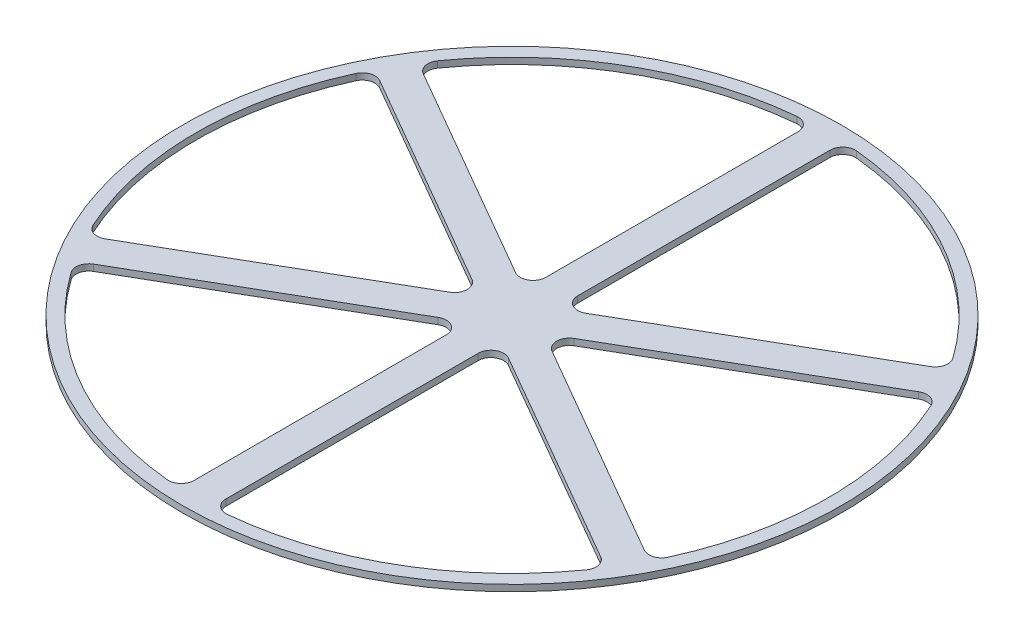
SolidWorks part; units mm, degrees
ref_plane "Front Plane" through (0, 0, 0) normal (0, 0, 1) x (1, 0, 0)
ref_plane "Top Plane" through (0, 0, 0) normal (0, 1, 0) x (1, 0, 0)
ref_plane "Right Plane" through (0, 0, 0) normal (1, 0, 0) x (0, 0, -1)
sketch "Sketch2" plane through (0, 0, 0) normal (0, 1, 0) x (1, 0, 0)
  line L0 (110.1965, 70.9543) -> (6.35, 10.9985)
  line L2 (-6.35, 130.9101) -> (-6.35, 10.9985)
  line L4 (6.35, 130.9101) -> (6.35, 10.9985)
  line L5 (116.5465, 59.9558) -> (12.7, 0)
  line L6 (116.5465, -59.9558) -> (12.7, 0)
  line L7 (110.1965, -70.9543) -> (6.35, -10.9985)
  line L8 (6.35, -130.9101) -> (6.35, -10.9985)
  line L9 (-6.35, -130.9101) -> (-6.35, -10.9985)
  line L10 (-110.1965, -70.9543) -> (-6.35, -10.9985)
  line L11 (-116.5465, -59.9558) -> (-12.7, 0)
  line L12 (-116.5465, 59.9558) -> (-12.7, 0)
  line L13 (-110.1965, 70.9543) -> (-6.35, 10.9985)
  arc A1 (6.35, 130.9101) -> (-6.35, 130.9101) centre (0, 0) ccw
  arc A4 (116.5465, 59.9558) -> (110.1965, 70.9543) centre (0, 0) ccw
  arc A6 (110.1965, -70.9543) -> (116.5465, -59.9558) centre (0, 0) ccw
  arc A8 (-6.35, -130.9101) -> (6.35, -130.9101) centre (0, 0) ccw
  arc A10 (-116.5465, -59.9558) -> (-110.1965, -70.9543) centre (0, 0) ccw
  arc A12 (-110.1965, 70.9543) -> (-116.5465, 59.9558) centre (0, 0) ccw
  point P1 (0, 131.064)
  point P36 (0, 0)
  dimension "D1" = 6
  dimension "D3" = 131.064
  dimension "D2" = 12.7
extrude "Boss-Extrude1" add sketch "Sketch2" along normal blind 2.54
sketch "Sketch3" plane through (0, 2.54, 0) normal (0, 1, 0) x (1, 0, 0)
  line L6 (-69.85, 110.8997) -> (-69.85, 104.5497)
  line L7 (69.85, 110.8997) -> (69.85, 104.5497)
  arc A0 (69.85, 110.8997) -> (-69.85, 110.8997) centre (0, 0) ccw
  arc A1 (6.35, 130.9101) -> (-6.35, 130.9101) centre (0, 0) ccw construction
  arc A2 (69.85, 104.5497) -> (-69.85, 104.5497) centre (0, 0) ccw
  point P9 (0, 131.064)
  dimension "D1" = 6.35
  dimension "D2" = 139.7
extrude "Boss-Extrude2" add sketch "Sketch3" against normal up to surface (2.54 mm away) up to face at (0, 0, 0)
pattern_circular "CirPattern1" count 6 every 60 about axis through (0, 2.54, 0) along (0, -1, 0) of "Boss-Extrude2"
fillet "Fillet1" radius 5.08 12 edges at (111.9271, 1.27, -57.2888) (105.5771, 1.27, -68.2873) (-6.35, 1.27, -125.5761) (6.35, 1.27, -125.5761) (-105.5771, 1.27, -68.2873) (-111.9271, 1.27, -57.2888) (-111.9271, 1.27, 57.2888) (-105.5771, 1.27, 68.2873) (-6.35, 1.27, 125.5761) (6.35, 1.27, 125.5761) (105.5771, 1.27, 68.2873) (111.9271, 1.27, 57.2888)
fillet "Fillet2" radius 5.08 6 edges at (-6.35, 1.27, -10.9985) (6.35, 1.27, -10.9985) (12.7, 1.27, 0) (6.35, 1.27, 10.9985) (-6.35, 1.27, 10.9985) (-12.7, 1.27, 0)
